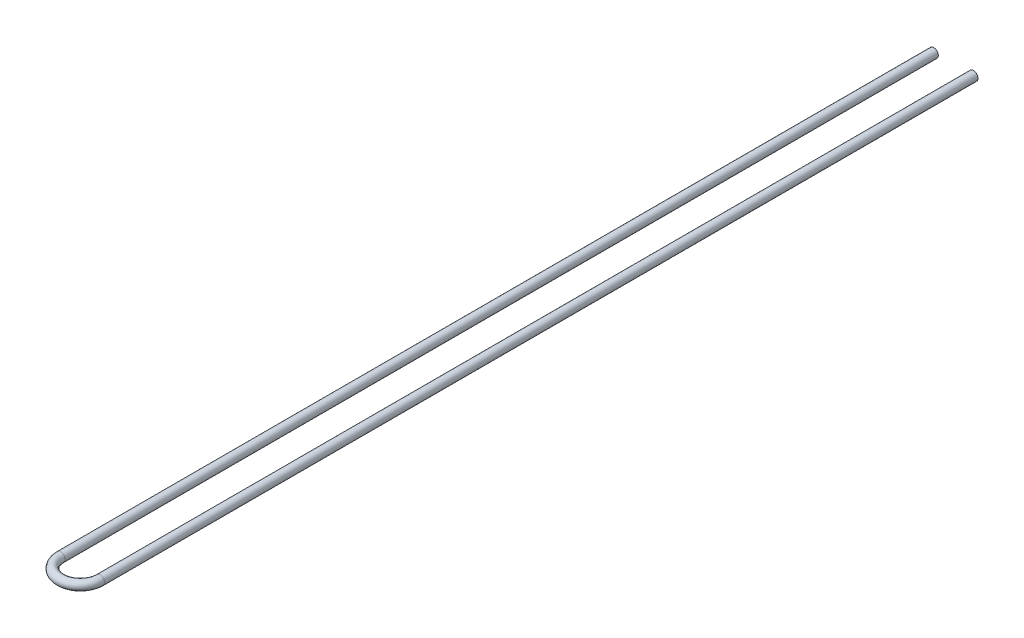
SolidWorks part; units mm, degrees
ref_plane "Front Plane" through (0, 0, 0) normal (0, 0, 1) x (1, 0, 0)
ref_plane "Top Plane" through (0, 0, 0) normal (0, 1, 0) x (1, 0, 0)
ref_plane "Right Plane" through (0, 0, 0) normal (1, 0, 0) x (0, 0, -1)
sketch "Sketch1" plane through (0, 0, 0) normal (0, 1, 0) x (1, 0, 0)
  line L0 (57.23, -300) -> (57.23, -2440)
  line L2 (-40, -300) -> (-40, -2440)
  arc A0 (-40, -2440) -> (57.23, -2440) centre (8.615, -2440) ccw
  dimension "D1" = 2140
  dimension "D2" = 97.23
ref_plane "Plane1" through (57.23, 0, 300) normal (0, 0, -1) x (-1, 0, 0)
sketch "Sketch2" plane through (57.23, 0, 300) normal (0, 0, -1) x (-1, 0, 0)
  circle A0 centre (0, 0) radius 9.95
  circle A1 centre (0, 0) radius 11.1
  dimension "D1" = 22.2
  dimension "D2" = 19.9
sweep "Sweep1" add profiles "Sketch2" path "Sketch1"
